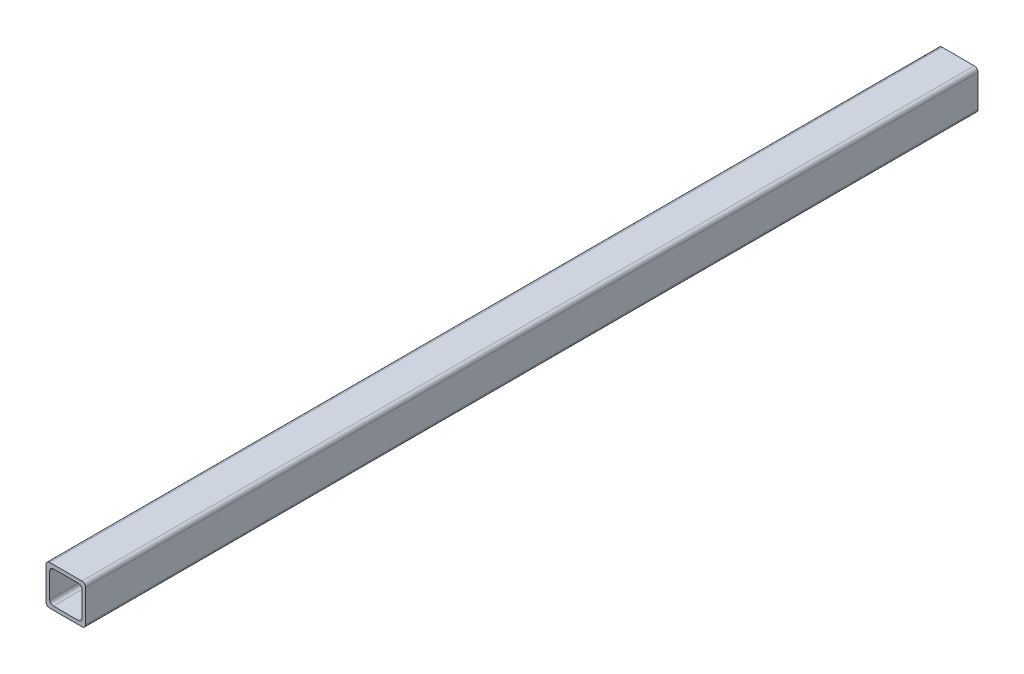
SolidWorks part; units mm, degrees
ref_plane "Front Plane" through (0, 0, 0) normal (0, 0, 1) x (1, 0, 0)
ref_plane "Top Plane" through (0, 0, 0) normal (0, 1, 0) x (1, 0, 0)
ref_plane "Right Plane" through (0, 0, 0) normal (1, 0, 0) x (0, 0, -1)
sketch "Sketch1" plane through (0, 0, 0) normal (0, 0, 1) x (1, 0, 0)
  line L1 (-8.46, -11) -> (8.46, -11)
  line L2 (-11, -8.46) -> (-11, 8.46)
  line L3 (-8.46, 11) -> (8.46, 11)
  line L4 (11, -8.46) -> (11, 8.46)
  line L5 (-11, -11) -> (11, 11) construction
  line L6 (-11, 11) -> (11, -11) construction
  line L7 (-11, -13.54) -> (11, -13.54)
  line L8 (-13.54, -11) -> (-13.54, 11)
  line L9 (-11, 13.54) -> (11, 13.54)
  line L10 (13.54, -11) -> (13.54, 11)
  line L11 (-13.54, -13.54) -> (13.54, 13.54) construction
  line L12 (-13.54, 13.54) -> (13.54, -13.54) construction
  arc A0 (11, -8.46) -> (8.46, -11) centre (8.46, -8.46) cw
  arc A1 (8.46, 11) -> (11, 8.46) centre (8.46, 8.46) cw
  arc A2 (-11, -8.46) -> (-8.46, -11) centre (-8.46, -8.46) ccw
  arc A3 (-11, 8.46) -> (-8.46, 11) centre (-8.46, 8.46) cw
  arc A4 (11, 13.54) -> (13.54, 11) centre (11, 11) cw
  arc A5 (11, -13.54) -> (13.54, -11) centre (11, -11) ccw
  arc A6 (-11, -13.54) -> (-13.54, -11) centre (-11, -11) cw
  arc A7 (-13.54, 11) -> (-11, 13.54) centre (-11, 11) cw
  point P0 (0, 0)
  point P18 (0, 0)
  dimension "D2" = 2.54
  dimension "D5" = 2.54
  dimension "D1" = 22
  dimension "D3" = 2.54
  dimension "D4" = 2.54
extrude "Boss-Extrude1" add sketch "Sketch1" along normal blind 609.6
